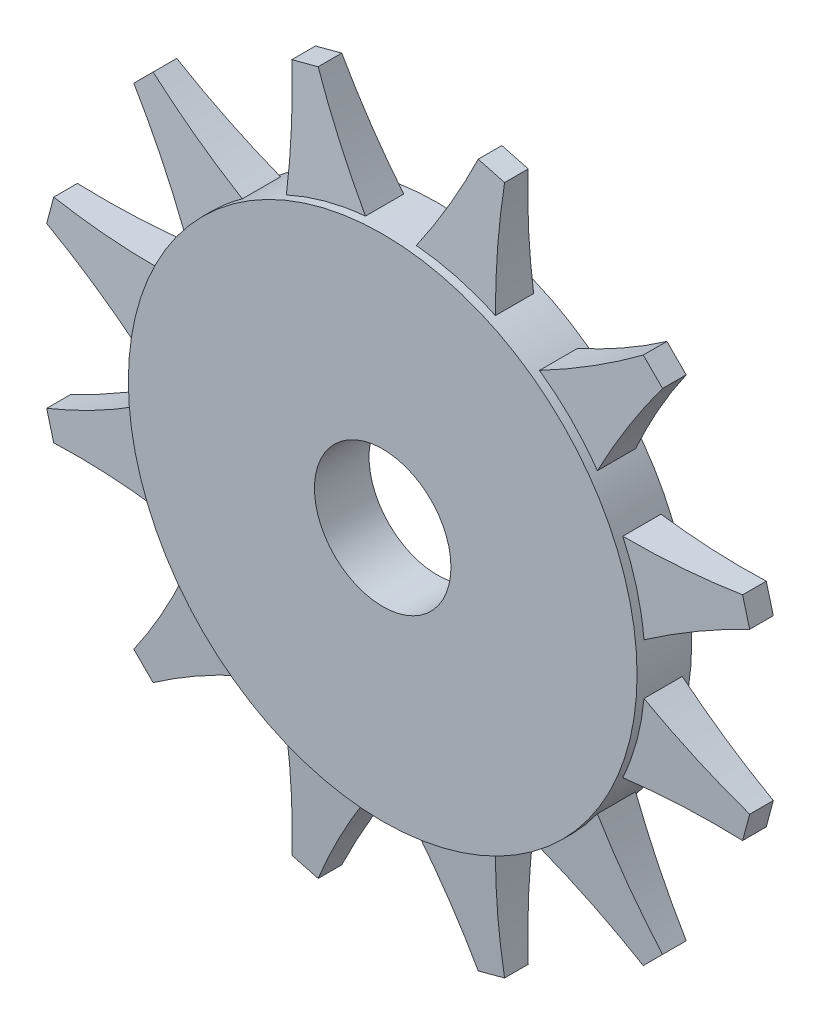
SolidWorks part; units mm, degrees
ref_plane "Front Plane" through (0, 0, 0) normal (0, 0, 1) x (1, 0, 0)
ref_plane "Top Plane" through (0, 0, 0) normal (0, 1, 0) x (1, 0, 0)
ref_plane "Right Plane" through (0, 0, 0) normal (1, 0, 0) x (0, 0, -1)
sketch "Sketch1" plane through (0, 0, 0) normal (0, 0, 1) x (1, 0, 0)
  line L0 (-11.5911, 0) -> (-10.0382, -5.7956)
  line L1 (11.5911, 0) -> (10.0382, 5.7956)
  line L2 (10.0382, 5.7956) -> (5.7956, 10.0382)
  line L3 (5.7956, 10.0382) -> (0, 11.5911)
  line L4 (0, 11.5911) -> (-5.7956, 10.0382)
  line L5 (-5.7956, 10.0382) -> (-10.0382, 5.7956)
  line L6 (-10.0382, 5.7956) -> (-11.5911, 0)
  line L7 (-10.0382, -5.7956) -> (-5.7956, -10.0382)
  line L8 (-5.7956, -10.0382) -> (0, -11.5911)
  line L9 (0, -11.5911) -> (5.7956, -10.0382)
  line L10 (5.7956, -10.0382) -> (10.0382, -5.7956)
  line L11 (10.0382, -5.7956) -> (11.5911, 0)
  circle A0 centre (0, 0) radius 11.1962 construction
  dimension "D1" = 6
sketch "Sketch3" plane through (0, 0, 0) normal (0, 0, 1) x (1, 0, 0)
  line L0 (0, 0) -> (-5.7956, 10.0382) construction
  line L1 (0, 0) -> (-10.0382, 5.7956) construction
  line L2 (-7.9169, 7.9169) -> (0, 0) construction
  line L3 (-5.7956, 10.0382) -> (-10.0382, 5.7956) construction
  line L4 (-7.5633, 5.442) -> (-5.442, 7.5633)
  line L5 (-9.6846, 8.9775) -> (-8.9775, 9.6846)
  circle A0 centre (0, 0) radius 11.5911
  spline S0 degree 2 poles (-9.6846, 8.9775) (-8.4734, 7.3002) (-7.5633, 5.442) knots 0 0 0 1 1 1
  spline S1 degree 2 poles (-8.9775, 9.6846) (-7.3002, 8.4734) (-5.442, 7.5633) knots 0 0 0 1 1 1
  point P13 (-6.5027, 6.5027)
  dimension "D2" = 2
  dimension "D5" = 4.1281
  dimension "D1" = 3
  dimension "D3" = 1
  dimension "D4" = 4
extrude "Boss-Extrude1" add sketch "Sketch3" along normal blind 2 contours S1 L5 S0 A0 | S1 A0 S0 L4
sketch3d "3DSketch1"
  line L0 (-6.5027, 6.5027, 0) -> (-6.5027, 6.5027, -1) construction
  line L1 (-7.5633, 5.442, 0) -> (-5.442, 7.5633, 0) construction
  dimension "D1" = 1
ref_plane "Plane1" through (0, 0, 0) normal (-0.7071, -0.7071, 0) x (0, 0, -1)
sketch "Sketch4" plane through (0, 0, 0) normal (-0.7071, -0.7071, 0) x (0, 0, -1)
  line L0 (0, -9.1962) -> (-0.3, -9.1962)
  line L1 (0, -9.1962) -> (0, -13.6962)
  line L2 (0, -13.6962) -> (-0.6, -13.6962)
  line L3 (-0.6, -13.6962) -> (-0.3, -9.1962)
  line L4 (-1.7, -9.1962) -> (-2, -9.1962)
  line L5 (-2, -9.1962) -> (-2, -13.6962)
  line L6 (-2, -13.6962) -> (-1.4, -13.6962)
  line L7 (-1.4, -13.6962) -> (-1.7, -9.1962)
  dimension "D1" = 0.3
  dimension "D2" = 0.6
  dimension "D3" = 4.5
  dimension "D4" = 0.3
  dimension "D5" = 0.6
  dimension "D6" = 4.5
  dimension "D7" = 2
extrude "Cut-Extrude1" cut sketch "Sketch4" against normal mid plane 4
sketch "Sketch5" plane through (0, 0, 0) normal (1, 0, 0) x (0, 0, -1)
  line L0 (0, 0) -> (2, 0) construction
  dimension "D1" = 2
pattern_circular "CirPattern1" count 12 over 360 about axis through (0, 0, 0) along (0, 0, -1) of bodies 102
sketch "Sketch6" plane through (0, 0, 0) normal (0, 0, 1) x (1, 0, 0)
  circle A0 centre (0, 0) radius 9.3177
  circle A1 centre (0, 0) radius 2.5
  dimension "D1" = 5
extrude "Boss-Extrude2" add sketch "Sketch6" along normal blind 2
ref_plane "Plane2" through (0, 0, 1) normal (0, 0, 1) x (1, 0, 0)
